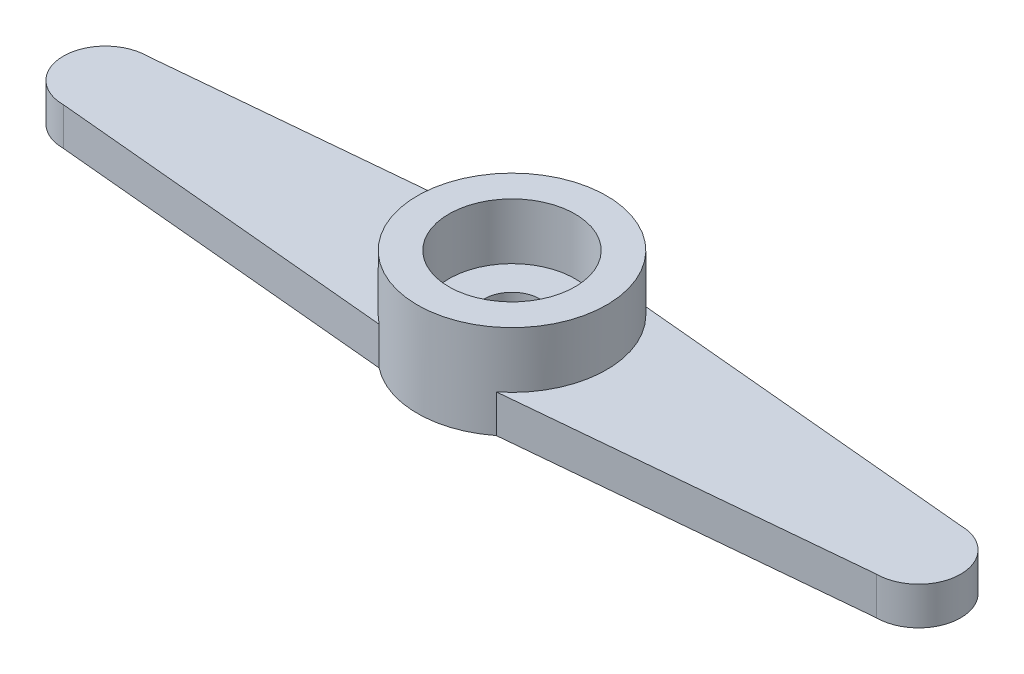
SolidWorks part; units mm, degrees
ref_plane "Piano frontale" through (0, 0, 0) normal (0, 0, 1) x (1, 0, 0)
ref_plane "Piano superiore" through (0, 0, 0) normal (0, 1, 0) x (1, 0, 0)
ref_plane "Piano destro" through (0, 0, 0) normal (1, 0, 0) x (0, 0, -1)
sketch "Schizzo1" plane through (0, 0, 0) normal (0, 1, 0) x (1, 0, 0)
  line L0 (-2.09, 2.65) -> (-14.5, 1.5)
  line L1 (-2.09, -2.65) -> (-14.5, -1.5)
  line L2 (-2.09, 2.65) -> (-2.09, -2.65)
  line L4 (2.09, 2.65) -> (2.09, -2.65)
  line L5 (2.09, -2.65) -> (14.5, -1.5)
  line L6 (2.09, 2.65) -> (14.5, 1.5)
  circle A0 centre (0, 0) radius 3.375
  arc A1 (-14.5, 1.5) -> (-14.5, -1.5) centre (-14.5, 0) ccw
  arc A2 (14.5, 1.5) -> (14.5, -1.5) centre (14.5, 0) cw
  point P8 (-2.09, 0)
  point P13 (-16, 0)
  point P14 (16, 0)
  point P18 (2.09, 0)
  dimension "D1" = 6.75
  dimension "D3" = 1.5
  dimension "D7" = 1.5
  dimension "D2" = 5.3
  dimension "D4" = 3
  dimension "D5" = 16
  dimension "D6" = 16
  dimension "D8" = 3
  dimension "D9" = 5.3
extrude "Estrusione-Estrusione1" add sketch "Schizzo1" along normal blind 1.35 contours L0 A1 L1 A0 | L2 A0 | L2 A0 | L4 A0 | A2 L6 A0 L5
sketch "Schizzo2" plane through (0, 1.35, 0) normal (0, 1, 0) x (1, 0, 0)
  circle A0 centre (0, 0) radius 3.375
  dimension "D1" = 6.75
extrude "Estrusione-Estrusione2" add sketch "Schizzo2" along normal blind 2
sketch "Schizzo3" plane through (0, 3.35, 0) normal (0, 1, 0) x (1, 0, 0)
  circle A0 centre (0, 0) radius 2.25
  dimension "D1" = 4.5
extrude "Taglio-Estrusione1" cut sketch "Schizzo3" against normal blind 2
sketch "Schizzo4" plane through (0, 1.35, 0) normal (0, 1, 0) x (1, 0, 0)
  circle A0 centre (0, 0) radius 1
  dimension "D1" = 2
extrude "Taglio-Estrusione2" cut sketch "Schizzo4" against normal through all
